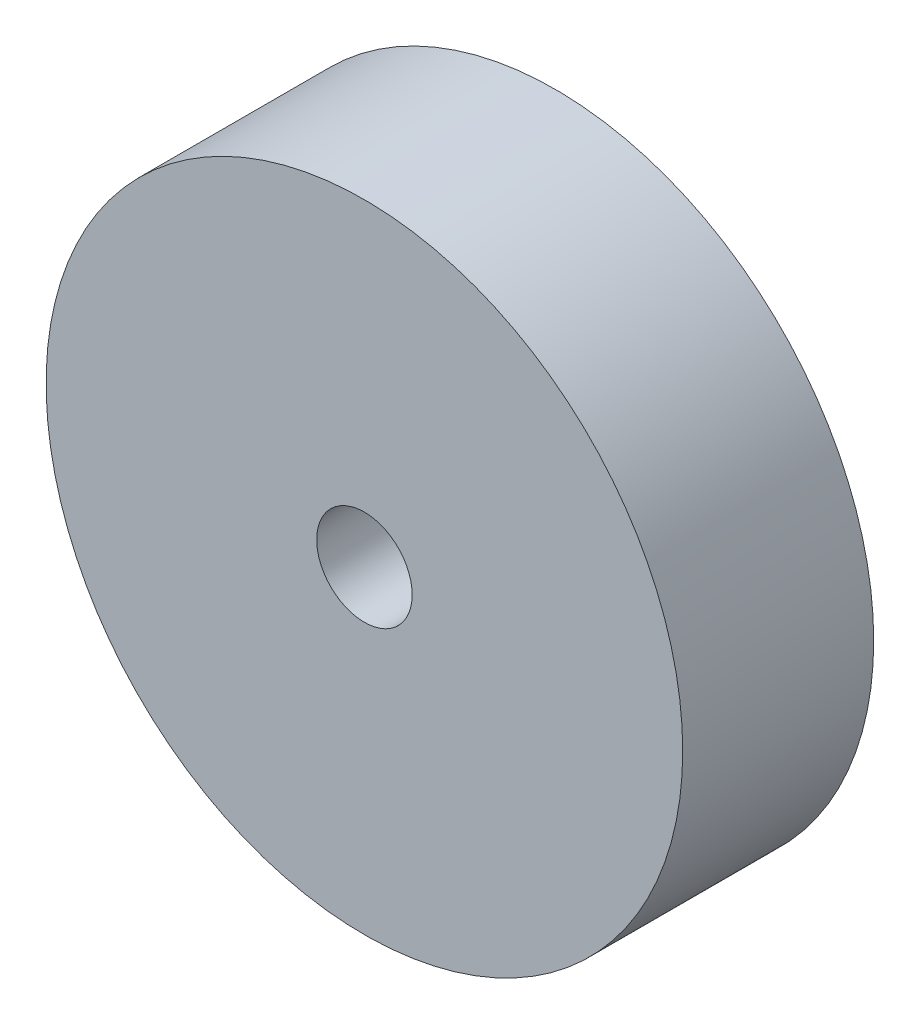
SolidWorks part; units mm, degrees
ref_plane "Front Plane" through (0, 0, 0) normal (0, 0, 1) x (1, 0, 0)
ref_plane "Top Plane" through (0, 0, 0) normal (0, 1, 0) x (1, 0, 0)
ref_plane "Right Plane" through (0, 0, 0) normal (1, 0, 0) x (0, 0, -1)
sketch "Sketch1" plane through (0, 0, 0) normal (0, 0, 1) x (1, 0, 0)
  circle A0 centre (0, 0) radius 5
  circle A1 centre (0, 0) radius 0.75
  dimension "D1" = 10
  dimension "D2" = 1.5
extrude "Boss-Extrude1" add sketch "Sketch1" along normal blind 3
